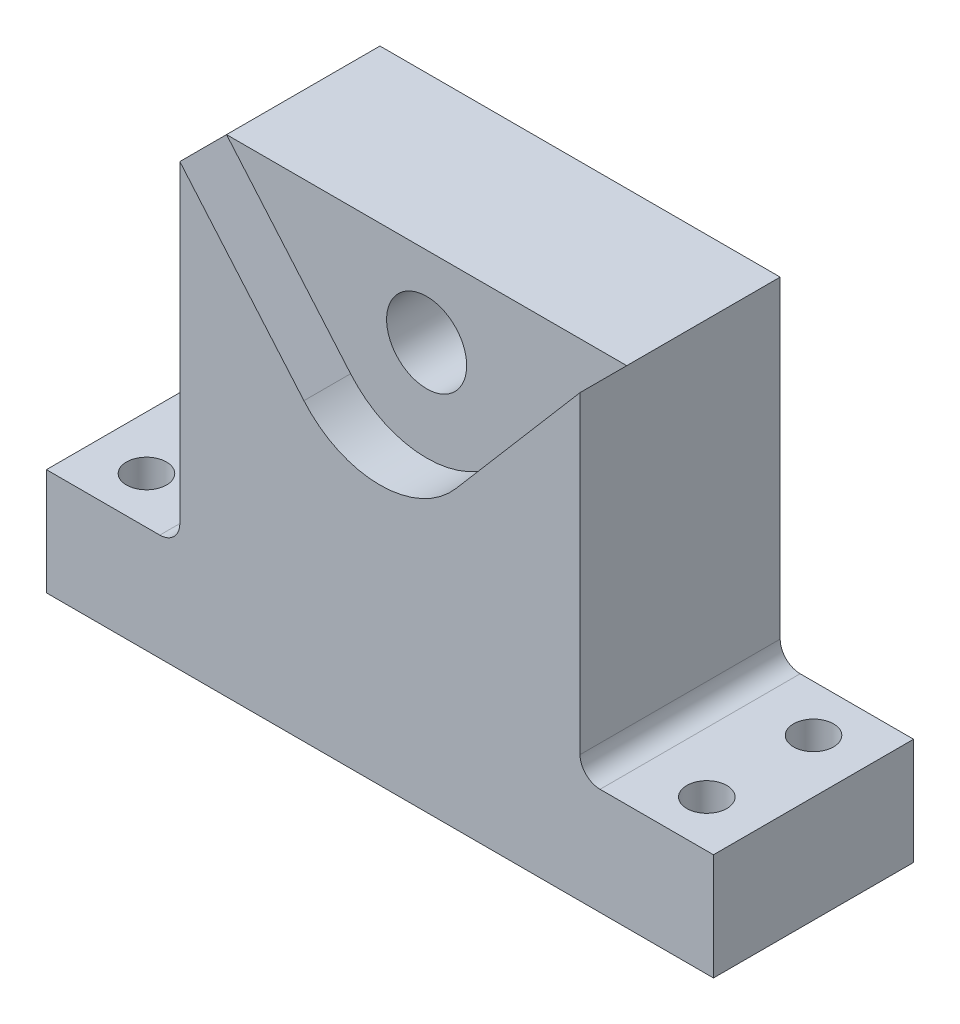
SolidWorks part; units mm, degrees
material "POM 乙缩醛共聚物"
ref_plane "前视基准面" through (0, 0, 0) normal (0, 0, 1) x (1, 0, 0)
ref_plane "上视基准面" through (0, 0, 0) normal (0, 1, 0) x (1, 0, 0)
ref_plane "右视基准面" through (0, 0, 0) normal (1, 0, 0) x (0, 0, -1)
sketch "草图1" plane through (0, 0, 0) normal (0, 0, 1) x (1, 0, 0)
  line L0 (0, 0) -> (0, 20.221) construction
  line L1 (25, 0) -> (-25, 0)
  line L2 (-25, 0) -> (-25, 8)
  line L3 (25, 0) -> (25, 8)
  line L4 (-25, 8) -> (-15, 8)
  line L5 (25, 8) -> (15, 8)
  line L6 (-15, 8) -> (-15, 33)
  line L7 (15, 8) -> (15, 33)
  line L8 (-15, 33) -> (15, 33)
  point P12 (0, 33)
  dimension "D1" = 8
  dimension "D2" = 30
  dimension "D3" = 50
  dimension "D4" = 25
extrude "凸台-拉伸1" add sketch "草图1" along normal blind 15
sketch "草图2" plane through (0, 0, 15) normal (0, 0, 1) x (1, 0, 0)
  line L0 (0, 33) -> (0, 0) construction
  line L1 (15, 33) -> (-15, 33) construction
  circle A0 centre (0, 27) radius 3
  dimension "D1" = 6
  dimension "D2" = 6
extrude "切除-拉伸1" cut sketch "草图2" against normal through all
sketch "草图3" plane through (0, 8, 0) normal (0, 1, 0) x (1, 0, 0)
  line L0 (21, 0) -> (21, -15) construction
  line L1 (25, 0) -> (15, 0) construction
  line L2 (25, -15) -> (15, -15) construction
  line L3 (0, 0) -> (0, -15) construction
  line L4 (15, -15) -> (-15, -15) construction
  line L5 (25, -15) -> (25, 0) construction
  line L6 (21, -7.5) -> (25, -7.5) construction
  circle A0 centre (21, -3.5) radius 1.5
  circle A1 centre (21, -11.5) radius 1.5
  circle A2 centre (-21, -11.5) radius 1.5
  circle A3 centre (-21, -3.5) radius 1.5
  dimension "D2" = 3
  dimension "D1" = 4
  dimension "D3" = 4
extrude "切除-拉伸2" cut sketch "草图3" against normal through all
fillet "圆角1" radius 1.5 2 edges at (-15, 8, 7.5) (15, 8, 7.5)
sketch "草图4" plane through (0, 0, 15) normal (0, 0, 1) x (1, 0, 0)
  line L0 (0, 0) -> (0, 33) construction
  line L1 (-25, 0) -> (25, 0) construction
  line L2 (15, 33) -> (-15, 33) construction
  line L3 (-15, 33) -> (-5.6998, 22.1254)
  line L4 (15, 33) -> (5.6998, 22.1254)
  line L5 (15, 33) -> (-15, 33)
  circle A0 centre (0, 27) radius 7.5
  circle M1 centre (0, 27) radius 3
  line M8 (15, 33) -> (-15, 33)
  dimension "D1" = 15
extrude "切除-拉伸3" cut sketch "草图4" against normal blind 3.5 contours A0 L3 M8 | A0 L0 M1 M8 | L0 A0 L5 M1 | A0 L4 M8
